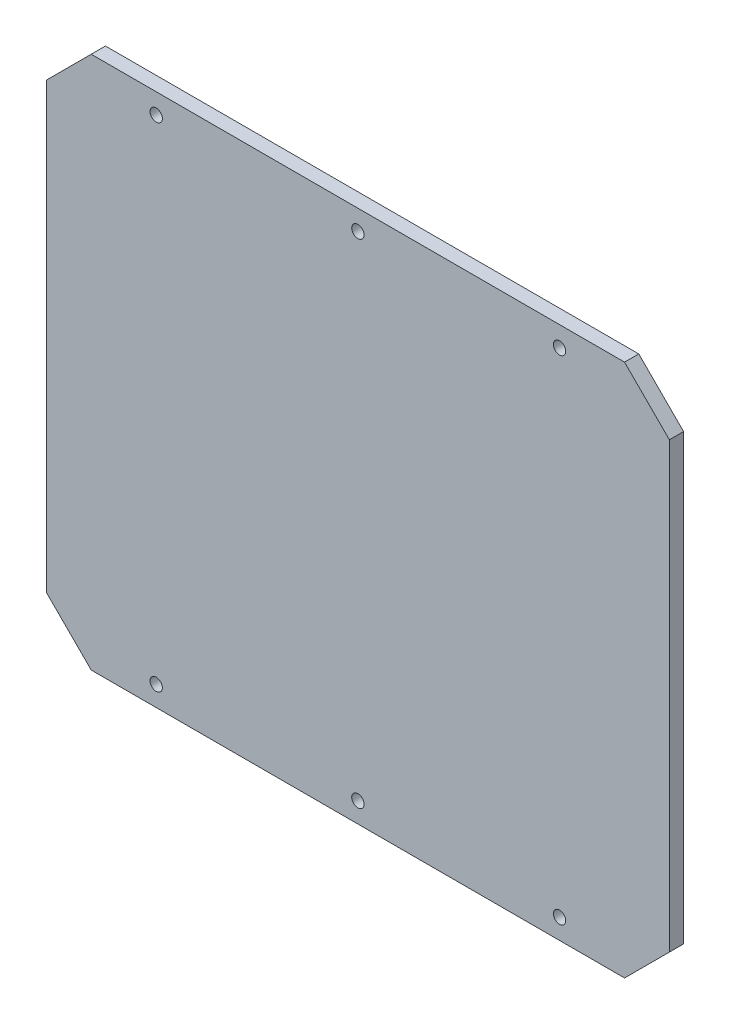
SolidWorks part; units mm, degrees
ref_plane "Front Plane" through (0, 0, 0) normal (0, 0, 1) x (1, 0, 0)
ref_plane "Top Plane" through (0, 0, 0) normal (0, 1, 0) x (1, 0, 0)
ref_plane "Right Plane" through (0, 0, 0) normal (1, 0, 0) x (0, 0, -1)
sketch "Sketch1" plane through (0, 0, 0) normal (0, 0, 1) x (1, 0, 0)
  line L0 (-79.0045, 0) -> (94.053, 0) construction
  line L1 (0, 67.0127) -> (0, -68.6587) construction
  line L3 (139, -119) -> (-139, -119)
  line L4 (139, -119) -> (139, 119)
  line L5 (139, 119) -> (-139, 119)
  line L6 (-139, -119) -> (-139, 119)
  line L7 (139, -119) -> (-139, 119) construction
  line L8 (139, 119) -> (-139, -119) construction
  point P4 (0, 0)
  dimension "D1" = 238
  dimension "D2" = 278
extrude "Boss-Extrude1" add sketch "Sketch1" along normal blind 6.35
chamfer "Chamfer1" distance 20 angle 45 4 edges at (139, -119, 3.175) (139, 119, 3.175) (-139, 119, 3.175) (-139, -119, 3.175)
sketch "Sketch4" plane through (0, 0, 6.35) normal (0, 0, 1) x (1, 0, 0)
  line L0 (0, 186.846) -> (0, -174.5938) construction
  line L1 (219.7737, 0) -> (-232.7917, 0) construction
  line L2 (119, 119) -> (-119, 119) construction
  line L3 (90, 110) -> (0, 110) construction
  circle A0 centre (-90, 110) radius 2.75
  circle A1 centre (0, 110) radius 2.75
  circle A2 centre (90, 110) radius 2.75
  circle A3 centre (90, -110) radius 2.75
  circle A4 centre (0, -110) radius 2.75
  circle A5 centre (-90, -110) radius 2.75
  dimension "D1" = 5.5
  dimension "D2" = 9
  dimension "D3" = 90
extrude "Cut-Extrude2" cut sketch "Sketch4" against normal blind 76.2
equation "\"plate_thickness\" = 6.35 'thickness of the plate "
equation "\"D1@Boss-Extrude1\"=\"plate_thickness\""
equation "\"connector_D1\" = 70 'the big holes diameter"
equation "\"mtg_hole_D\" = 5.5 'mounting holes"
equation "\"mtg_dfc\" = 40 'mounting hole distance from center"
equation "\"t_height\" = 200"
equation "\"t_width\" = 240"
equation "\"t_length\" = 240"
equation "\"plate_hole_from_edge\" = 9"
equation "\"plate_spacing\" = 1"
equation "\"front_plate_height\" = \"t_height\" + 38"
equation "\"front_plate_width\" = \"t_width\" + 38"
equation "\"side_plate_height\" = \"front_plate_height\""
equation "\"side_plate_length\" = \"t_length\" + 38"
equation "\"top_plate_width\" = \"front_plate_width\""
equation "\"top_plate_length\" = \"side_plate_length\""
equation "\"D2@Sketch1\"=\"side_plate_length\""
equation "\"D1@Sketch1\"=\"side_plate_height\""
equation "\"D2@Sketch4\"=\"plate_hole_from_edge\""
equation "\"D1@Sketch4\"=\"mtg_hole_D\""
